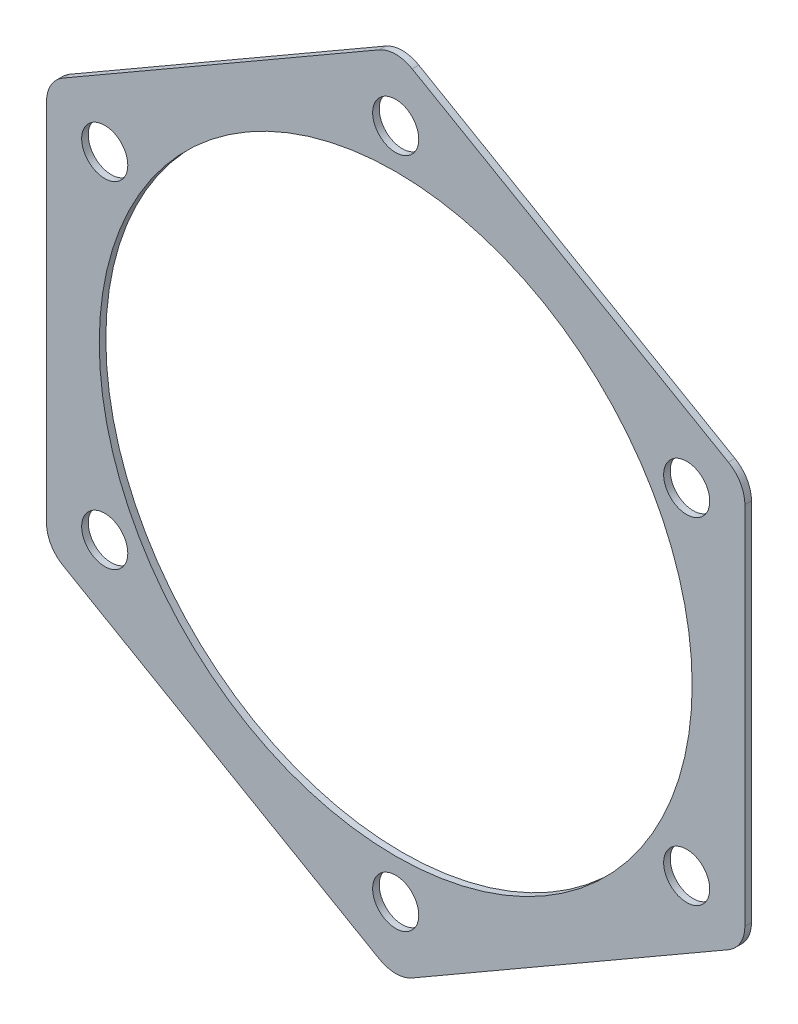
SolidWorks part; units mm, degrees
ref_plane "Front Plane" through (0, 0, 0) normal (0, 0, 1) x (1, 0, 0)
ref_plane "Top Plane" through (0, 0, 0) normal (0, 1, 0) x (1, 0, 0)
ref_plane "Right Plane" through (0, 0, 0) normal (1, 0, 0) x (0, 0, -1)
sketch "Sketch1" plane through (0, 0, 0) normal (0, 0, 1) x (1, 0, 0)
  line L1 (2.5, -59.7558) -> (50.5, -32.0429)
  line L2 (53, -27.7128) -> (53, 27.7128)
  line L3 (50.5, 32.0429) -> (2.5, 59.7558)
  line L4 (-2.5, 59.7558) -> (-50.5, 32.0429)
  line L5 (-53, 27.7128) -> (-53, -27.7128)
  line L6 (-50.5, -32.0429) -> (-2.5, -59.7558)
  circle A0 centre (0, 0) radius 53 construction
  circle A1 centre (0, 0) radius 51 construction
  circle A2 centre (0, 0) radius 45
  circle A3 centre (0, 51) radius 3.5
  circle A4 centre (44.1673, 25.5) radius 3.5
  circle A5 centre (44.1673, -25.5) radius 3.5
  circle A6 centre (0, -51) radius 3.5
  circle A7 centre (-44.1673, -25.5) radius 3.5
  circle A8 centre (-44.1673, 25.5) radius 3.5
  arc A9 (-53, 27.7128) -> (-50.5, 32.0429) centre (-48, 27.7128) cw
  arc A10 (-53, -27.7128) -> (-50.5, -32.0429) centre (-48, -27.7128) ccw
  arc A11 (-2.5, -59.7558) -> (2.5, -59.7558) centre (0, -55.4256) ccw
  arc A12 (50.5, -32.0429) -> (53, -27.7128) centre (48, -27.7128) ccw
  arc A13 (53, 27.7128) -> (50.5, 32.0429) centre (48, 27.7128) ccw
  arc A14 (2.5, 59.7558) -> (-2.5, 59.7558) centre (0, 55.4256) ccw
  point P26 (0, 0)
  point P28 (-53, -30.5996)
  point P33 (53, -30.5996)
  point P38 (0, 61.1991)
  dimension "D2" = 102
  dimension "D3" = 90
  dimension "D4" = 7
  dimension "D6" = 5
  dimension "D1" = 106
  dimension "D5" = 6
extrude "Boss-Extrude1" add sketch "Sketch1" along normal blind 1
